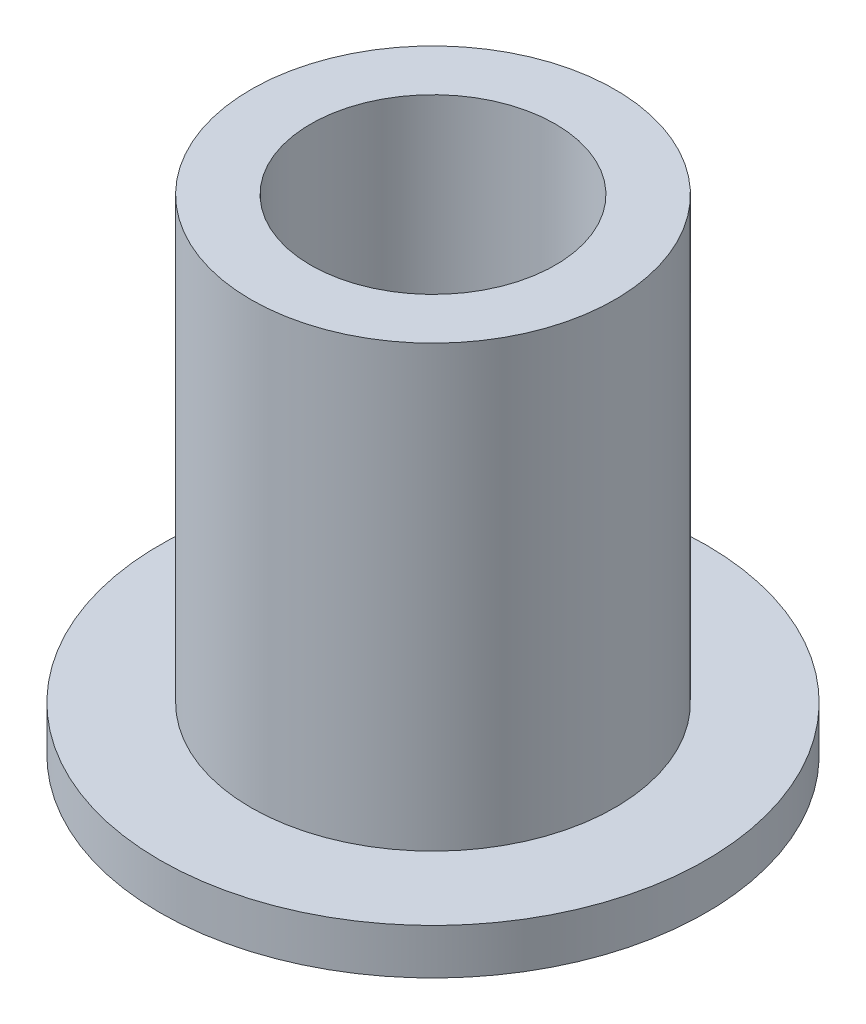
SolidWorks part; units mm, degrees
ref_plane "Front" through (0, 0, 0) normal (0, 0, 1) x (1, 0, 0)
ref_plane "Top" through (0, 0, 0) normal (0, 1, 0) x (1, 0, 0)
ref_plane "Right" through (0, 0, 0) normal (1, 0, 0) x (0, 0, -1)
sketch "Sketch1" plane through (0, 0, 0) normal (0, 1, 0) x (1, 0, 0)
  circle A0 centre (0, 0) radius 3.2004
  circle A1 centre (0, 0) radius 4.7625
  circle A2 centre (0, 0) radius 7.1438
  dimension "ID" = 6.4008
  dimension "OD" = 9.525
  dimension "FlangeOD" = 14.2875
sketch "Sketch2" plane through (0, 0, 0) normal (0, 1, 0) x (1, 0, 0)
  circle A0 centre (0, 0) radius 3.2004 construction
  circle A1 centre (0, 0) radius 4.7625 construction
  circle A2 centre (0, 0) radius 3.2004
  circle A3 centre (0, 0) radius 4.7625
extrude "Boss-Extrude1" add sketch "Sketch2" along normal blind 12.7
sketch "Sketch3" plane through (0, 0, 0) normal (0, 1, 0) x (1, 0, 0)
  circle A0 centre (0, 0) radius 7.1438 construction
  circle A1 centre (0, 0) radius 4.7625 construction
  circle A2 centre (0, 0) radius 7.1438
  circle A3 centre (0, 0) radius 4.7625
extrude "Boss-Extrude2" add sketch "Sketch3" along normal blind 1.1906
